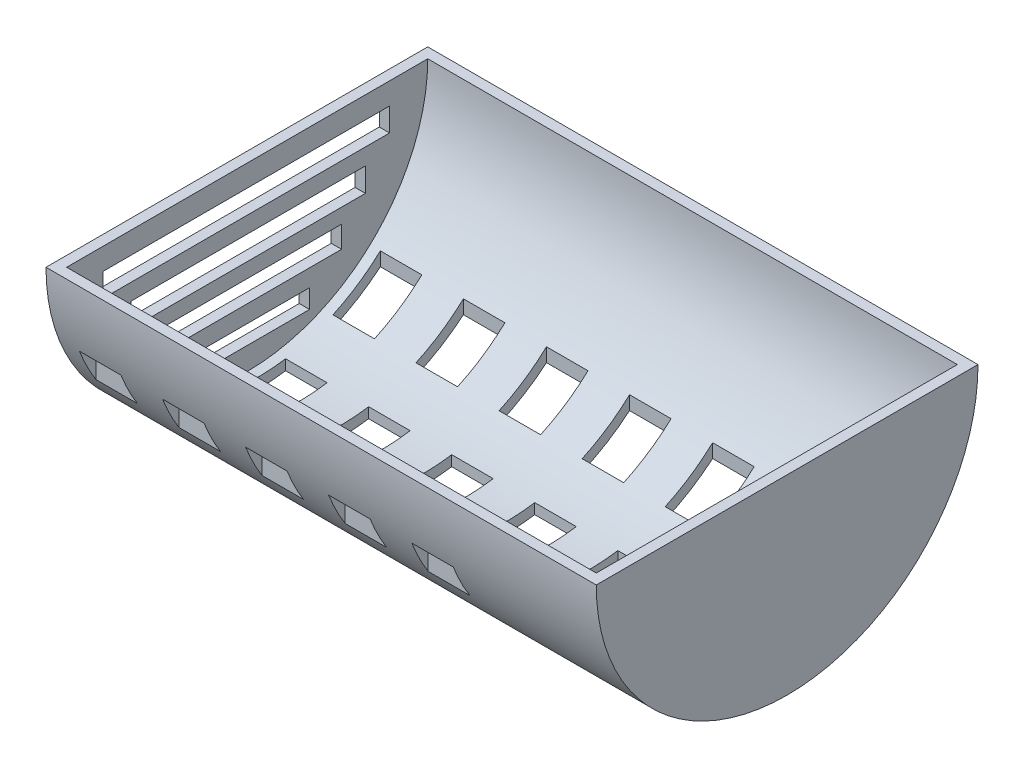
SolidWorks part; units mm, degrees
ref_plane "前视基准面" through (0, 0, 0) normal (0, 0, 1) x (1, 0, 0)
ref_plane "上视基准面" through (0, 0, 0) normal (0, 1, 0) x (1, 0, 0)
ref_plane "右视基准面" through (0, 0, 0) normal (1, 0, 0) x (0, 0, -1)
sketch "草图1" plane through (0, 0, 0) normal (0, 1, 0) x (1, 0, 0)
  line L0 (-95.7563, 0) -> (119.1586, 0) construction
  line L1 (-81.9246, 55.5) -> (78.0754, 55.5)
  line L2 (-81.9246, 55.5) -> (-81.9246, -55.5)
  line L3 (-81.9246, -55.5) -> (78.0754, -55.5)
  line L4 (78.0754, 55.5) -> (78.0754, -55.5)
  line L5 (-78.9246, 52.5) -> (75.0754, 52.5)
  line L6 (75.0754, 52.5) -> (75.0754, -52.5)
  line L7 (-78.9246, -52.5) -> (75.0754, -52.5)
  line L8 (-78.9246, 52.5) -> (-78.9246, -52.5)
  point P0 (0, 0)
  dimension "D3" = 3
  dimension "D1" = 111
  dimension "D2" = 160
revolve "旋转1" add sketch "草图1" angle 180 about L0
sketch "草图6" plane through (0, 0, 0) normal (0, 1, 0) x (1, 0, 0)
  line L0 (0, 63.8905) -> (0, 49.5) construction
  line L2 (-75.9246, 49.5) -> (-63.8479, 49.5)
  line L3 (-81.9246, 55.5) -> (78.0754, 55.5) construction
  line L4 (-75.9246, 35.7174) -> (-63.8479, 35.7174)
  line L5 (-75.9246, 21.9347) -> (-63.8479, 21.9347)
  line L6 (-75.9246, 8.1521) -> (-63.8479, 8.1521)
  line L7 (-75.9246, -5.6305) -> (-63.8479, -5.6305)
  line L8 (-75.9246, -19.4132) -> (-63.8479, -19.4132)
  line L9 (-75.9246, -33.1958) -> (-63.8479, -33.1958)
  line L10 (-75.9246, -46.9784) -> (-63.8479, -46.9784)
  line L12 (-75.9246, 63.8905) -> (-75.9246, 49.5)
  line L13 (-81.9246, -55.5) -> (-81.9246, 55.5) construction
  line L14 (-63.8479, 63.8905) -> (-63.8479, 49.5)
  line L15 (-51.7712, 63.8905) -> (-51.7712, 49.5)
  line L16 (-39.6945, 63.8905) -> (-39.6945, 49.5)
  line L17 (-27.6178, 63.8905) -> (-27.6178, 49.5)
  line L18 (-15.5412, 63.8905) -> (-15.5412, 49.5)
  line L19 (-3.4645, 63.8905) -> (-3.4645, 49.5)
  line L20 (8.6122, 63.8905) -> (8.6122, 49.5)
  line L21 (20.6889, 63.8905) -> (20.6889, 49.5)
  line L22 (32.7656, 63.8905) -> (32.7656, 49.5)
  line L26 (-75.9246, 63.8905) -> (-63.8479, 63.8905)
  line L30 (-51.7712, 63.8905) -> (-39.6945, 63.8905)
  line L31 (-27.6178, 63.8905) -> (-15.5412, 63.8905)
  line L32 (-3.4645, 63.8905) -> (8.6122, 63.8905)
  line L33 (20.6889, 63.8905) -> (32.7656, 63.8905)
  line L38 (-63.8479, -69.8163) -> (-75.9246, -69.8163)
  line L39 (-39.6945, -69.8163) -> (-51.7712, -69.8163)
  line L40 (-15.5412, -69.8163) -> (-27.6178, -69.8163)
  line L41 (8.6122, -69.8163) -> (-3.4645, -69.8163)
  line L42 (32.7656, -69.8163) -> (20.6889, -69.8163)
  line L46 (-75.9246, 35.7174) -> (-75.9246, 21.9347)
  line L47 (-63.8479, 35.7174) -> (-63.8479, 21.9347)
  line L48 (-51.7712, 35.7174) -> (-51.7712, 21.9347)
  line L49 (68.9956, 49.5) -> (68.9956, 37.5) [skipped]
  line L50 (56.9189, 49.5) -> (56.9189, 37.5) [skipped]
  line L51 (44.8423, 49.5) -> (44.8423, 37.5) [skipped]
  line L52 (-39.6945, 35.7174) -> (-39.6945, 21.9347)
  line L53 (-27.6178, 35.7174) -> (-27.6178, 21.9347)
  line L54 (-63.9246, -60.7611) -> (-51.9246, -60.7611) [skipped]
  line L55 (-15.5412, 35.7174) -> (-15.5412, 21.9347)
  line L56 (-3.4645, 35.7174) -> (-3.4645, 21.9347)
  line L57 (0, 35.7174) -> (0, 21.9347) construction
  line L58 (8.6122, 35.7174) -> (8.6122, 21.9347)
  line L59 (20.6889, 35.7174) -> (20.6889, 21.9347)
  line L60 (32.7656, 35.7174) -> (32.7656, 21.9347)
  line L61 (-51.7712, 49.5) -> (-39.6945, 49.5)
  line L62 (-27.6178, 49.5) -> (-15.5412, 49.5)
  line L63 (-3.4645, 49.5) -> (8.6122, 49.5)
  line L64 (20.6889, 49.5) -> (32.7656, 49.5)
  line L65 (-75.9246, 8.1521) -> (-75.9246, -5.6305)
  line L66 (-63.8479, 8.1521) -> (-63.8479, -5.6305)
  line L67 (-51.7712, 8.1521) -> (-51.7712, -5.6305)
  line L68 (-39.6945, 8.1521) -> (-39.6945, -5.6305)
  line L69 (-27.6178, 8.1521) -> (-27.6178, -5.6305)
  line L70 (-15.5412, 8.1521) -> (-15.5412, -5.6305)
  line L71 (-3.4645, 8.1521) -> (-3.4645, -5.6305)
  line L72 (0, 8.1521) -> (0, -5.6305) construction
  line L73 (8.6122, 8.1521) -> (8.6122, -5.6305)
  line L74 (20.6889, 8.1521) -> (20.6889, -5.6305)
  line L75 (32.7656, 8.1521) -> (32.7656, -5.6305)
  line L76 (32.7656, -19.4132) -> (32.7656, -33.1958)
  line L77 (20.6889, -19.4132) -> (20.6889, -33.1958)
  line L78 (8.6122, -19.4132) -> (8.6122, -33.1958)
  line L79 (0, -19.4132) -> (0, -33.1958) construction
  line L80 (-3.4645, -19.4132) -> (-3.4645, -33.1958)
  line L81 (-15.5412, -19.4132) -> (-15.5412, -33.1958)
  line L82 (-27.6178, -19.4132) -> (-27.6178, -33.1958)
  line L83 (-39.6945, -19.4132) -> (-39.6945, -33.1958)
  line L84 (-51.7712, -19.4132) -> (-51.7712, -33.1958)
  line L85 (-63.8479, -19.4132) -> (-63.8479, -33.1958)
  line L86 (-75.9246, -19.4132) -> (-75.9246, -33.1958)
  line L87 (-75.9246, -46.9784) -> (-75.9246, -69.8163)
  line L88 (-63.8479, -46.9784) -> (-63.8479, -69.8163)
  line L89 (-51.7712, -46.9784) -> (-51.7712, -69.8163)
  line L90 (-39.6945, -46.9784) -> (-39.6945, -69.8163)
  line L91 (-27.6178, -46.9784) -> (-27.6178, -69.8163)
  line L92 (-15.5412, -46.9784) -> (-15.5412, -69.8163)
  line L93 (-3.4645, -46.9784) -> (-3.4645, -69.8163)
  line L94 (0, -46.5) -> (0, -68.19) construction
  line L95 (8.6122, -46.9784) -> (8.6122, -69.8163)
  line L96 (20.6889, -46.9784) -> (20.6889, -69.8163)
  line L97 (32.7656, -46.9784) -> (32.7656, -69.8163)
  line L98 (-51.7712, 35.7174) -> (-39.6945, 35.7174)
  line L99 (-51.7712, 21.9347) -> (-39.6945, 21.9347)
  line L100 (-51.7712, 8.1521) -> (-39.6945, 8.1521)
  line L101 (-51.7712, 0) -> (-39.6945, 0) construction
  line L102 (-51.7712, -5.6305) -> (-39.6945, -5.6305)
  line L103 (-51.7712, -19.4132) -> (-39.6945, -19.4132)
  line L104 (-51.7712, -33.1958) -> (-39.6945, -33.1958)
  line L105 (-51.7712, -46.9784) -> (-39.6945, -46.9784)
  line L106 (-27.6178, 35.7174) -> (-15.5412, 35.7174)
  line L107 (-27.6178, 21.9347) -> (-15.5412, 21.9347)
  line L108 (-27.6178, 8.1521) -> (-15.5412, 8.1521)
  line L109 (-27.6178, 0) -> (-15.5412, 0) construction
  line L110 (-27.6178, -5.6305) -> (-15.5412, -5.6305)
  line L111 (-27.6178, -19.4132) -> (-15.5412, -19.4132)
  line L112 (-27.6178, -33.1958) -> (-15.5412, -33.1958)
  line L113 (-27.6178, -46.9784) -> (-15.5412, -46.9784)
  line L114 (-3.4645, 35.7174) -> (8.6122, 35.7174)
  line L115 (-3.4645, 21.9347) -> (8.6122, 21.9347)
  line L116 (-3.4645, 8.1521) -> (8.6122, 8.1521)
  line L117 (-3.4645, 0) -> (8.6122, 0) construction
  line L118 (-3.4645, -5.6305) -> (8.6122, -5.6305)
  line L119 (-3.4645, -19.4132) -> (8.6122, -19.4132)
  line L120 (-3.4645, -33.1958) -> (8.6122, -33.1958)
  line L121 (-3.4645, -46.9784) -> (8.6122, -46.9784)
  line L122 (20.6889, 35.7174) -> (32.7656, 35.7174)
  line L123 (20.6889, 21.9347) -> (32.7656, 21.9347)
  line L124 (20.6889, 8.1521) -> (32.7656, 8.1521)
  line L125 (20.6889, 0) -> (44.0754, 0) construction
  line L126 (20.6889, -5.6305) -> (32.7656, -5.6305)
  line L127 (20.6889, -19.4132) -> (32.7656, -19.4132)
  line L128 (20.6889, -33.1958) -> (32.7656, -33.1958)
  line L129 (20.6889, -46.9784) -> (32.7656, -46.9784)
  dimension "D1" = 6
  dimension "D3" = 6
  dimension "D2" = 9
  dimension "D4" = 13
extrude "切除-拉伸3" cut sketch "草图6" along normal blind 80 from offset 100 offset against normal yes
sketch "草图7" plane through (-81.9246, 0, 0) normal (-1, 0, 0) x (0, 0, 1)
  line L1 (-41.4009, -6.3337) -> (41.8782, -6.3337)
  line L2 (-41.4009, -6.3337) -> (-41.4009, -13.1344)
  line L3 (-41.4009, -13.1344) -> (41.8782, -13.1344)
  line L4 (41.8782, -6.3337) -> (41.8782, -13.1344)
  line L5 (-34.3616, -17.9068) -> (33.765, -17.9068)
  line L6 (-34.3616, -17.9068) -> (-34.3616, -24.8269)
  line L7 (-34.3616, -24.8269) -> (33.765, -24.8269)
  line L8 (33.765, -17.9068) -> (33.765, -24.8269)
  line L9 (-27.4415, -29.1221) -> (29.4698, -29.1221)
  line L10 (-27.4415, -29.1221) -> (-27.4415, -35.4456)
  line L11 (-27.4415, -35.4456) -> (29.4698, -35.4456)
  line L12 (29.4698, -29.1221) -> (29.4698, -35.4456)
  line L13 (-18.1353, -40.4566) -> (20.0443, -40.4566)
  line L14 (-18.1353, -40.4566) -> (-18.1353, -45.9449)
  line L15 (-18.1353, -45.9449) -> (20.0443, -45.9449)
  line L16 (20.0443, -40.4566) -> (20.0443, -45.9449)
extrude "切除-拉伸4" cut sketch "草图7" against normal blind 80
